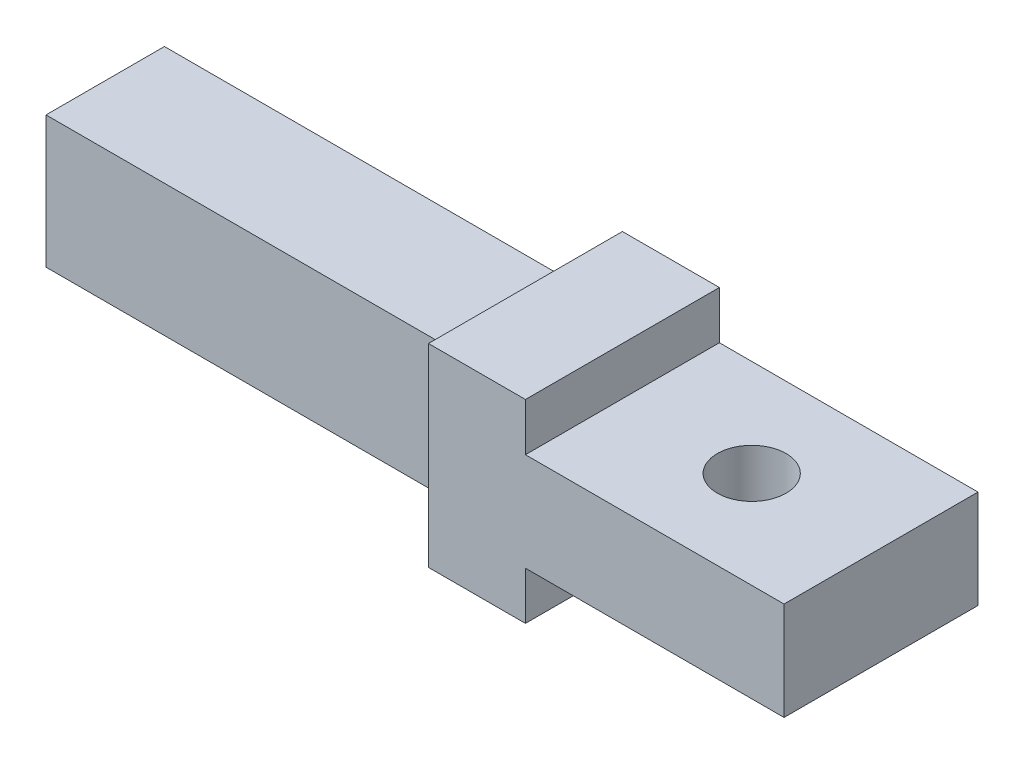
SolidWorks part; units mm, degrees
ref_plane "Front Plane" through (0, 0, 0) normal (0, 0, 1) x (1, 0, 0)
ref_plane "Top Plane" through (0, 0, 0) normal (0, 1, 0) x (1, 0, 0)
ref_plane "Right Plane" through (0, 0, 0) normal (1, 0, 0) x (0, 0, -1)
sketch "Sketch1" plane through (0, 0, 0) normal (1, 0, 0) x (0, 0, -1)
  line L1 (0, 0) -> (19.05, 0)
  line L2 (0, 0) -> (0, 19.05)
  line L3 (0, 19.05) -> (19.05, 19.05)
  line L4 (19.05, 0) -> (19.05, 19.05)
  line L5 (0, 0) -> (19.05, 19.05) construction
  line L6 (0, 19.05) -> (19.05, 0) construction
  point P4 (9.525, 9.525)
  dimension "D1" = 19.05
  dimension "D2" = 19.05
extrude "Boss-Extrude1" add sketch "Sketch1" along normal blind 76.2
sketch "Sketch2" plane through (0, 0, 0) normal (0, 0, 1) x (1, 0, 0)
  line L1 (76.2, 19.05) -> (50.8, 19.05)
  line L2 (76.2, 19.05) -> (76.2, 14.351)
  line L3 (76.2, 14.351) -> (50.8, 14.351)
  line L4 (50.8, 19.05) -> (50.8, 14.351)
  line L5 (76.2, 19.05) -> (50.8, 14.351) construction
  line L6 (76.2, 14.351) -> (50.8, 19.05) construction
  line L7 (76.2, 0) -> (50.8, 0)
  line L8 (76.2, 0) -> (76.2, 4.699)
  line L9 (76.2, 4.699) -> (50.8, 4.699)
  line L10 (50.8, 0) -> (50.8, 4.699)
  line L11 (76.2, 0) -> (50.8, 4.699) construction
  line L12 (76.2, 4.699) -> (50.8, 0) construction
  point P4 (63.5, 16.7005)
  point P10 (63.5, 2.3495)
  dimension "D1" = 9.652
  dimension "D2" = 25.4
extrude "Cut-Extrude1" cut sketch "Sketch2" against normal through all
sketch "Sketch3" plane through (0, 0, 0) normal (0, 0, 1) x (1, 0, 0)
  line L0 (50.8, 14.351) -> (76.2, 14.351) construction
  line L1 (0, 19.05) -> (41.275, 19.05)
  line L2 (0, 19.05) -> (0, 16.002)
  line L3 (0, 16.002) -> (41.275, 16.002)
  line L4 (41.275, 19.05) -> (41.275, 16.002)
  line L5 (0, 19.05) -> (41.275, 16.002) construction
  line L6 (0, 16.002) -> (41.275, 19.05) construction
  line L7 (0, 0) -> (41.275, 0)
  line L8 (0, 0) -> (0, 3.048)
  line L9 (0, 3.048) -> (41.275, 3.048)
  line L10 (41.275, 0) -> (41.275, 3.048)
  line L11 (0, 0) -> (41.275, 3.048) construction
  line L12 (0, 3.048) -> (41.275, 0) construction
  point P4 (20.6375, 17.526)
  point P10 (20.6375, 1.524)
  point P12 (63.5, 14.351)
  dimension "D1" = 22.225
  dimension "D2" = 12.954
extrude "Cut-Extrude2" cut sketch "Sketch3" against normal through all
sketch "Sketch4" plane through (0, 16.002, 0) normal (0, 1, 0) x (1, 0, 0)
  line L0 (41.275, 19.05) -> (41.275, 0) construction
  line L1 (0, 19.05) -> (41.275, 19.05)
  line L2 (0, 19.05) -> (0, 15.3416)
  line L3 (0, 15.3416) -> (41.275, 15.3416)
  line L4 (41.275, 19.05) -> (41.275, 15.3416)
  line L5 (0, 19.05) -> (41.275, 15.3416) construction
  line L6 (0, 15.3416) -> (41.275, 19.05) construction
  line L7 (0, 0) -> (41.275, 0)
  line L8 (0, 0) -> (0, 3.7084)
  line L9 (0, 3.7084) -> (41.275, 3.7084)
  line L10 (41.275, 0) -> (41.275, 3.7084)
  line L11 (0, 0) -> (41.275, 3.7084) construction
  line L12 (0, 3.7084) -> (41.275, 0) construction
  point P4 (20.6375, 17.1958)
  point P10 (20.6375, 1.8542)
  dimension "D1" = 11.6332
extrude "Cut-Extrude3" cut sketch "Sketch4" against normal through all
sketch "Sketch5" plane through (0, 14.351, 0) normal (0, 1, 0) x (1, 0, 0)
  line L0 (76.2, 19.05) -> (76.2, 0) construction
  line L1 (50.8, 19.05) -> (76.2, 19.05) construction
  point P0 (63.5, 9.525)
  dimension "D1" = 12.7
  dimension "D2" = 9.525
sketch "Sketch8" plane through (0, 14.351, 0) normal (0, 1, 0) x (1, 0, 0)
  point P0 (63.5, 9.525)
hole_wizard "1/4 Clearance Hole1" positions "Sketch8" profile "Sketch7" hole size "1/4" standard "ANSI Inch" end condition through all
sketch "Sketch7" plane through (63.5, 14.351, -9.525) normal (1, 0, 0) x (0, 0, 1)
  line L0 (0, 0) -> (0, 14.351)
  line L1 (0, 14.351) -> (3.3782, 14.351)
  line L2 (3.3782, 14.351) -> (3.3782, 0)
  line L5 (3.3782, 0) -> (0, 0)
  line L11 (0, -6.35) -> (0, 107.95) construction
  dimension "Thru Hole Dia." = 6.7564
  dimension "Thru Hole Depth" = 14.351
